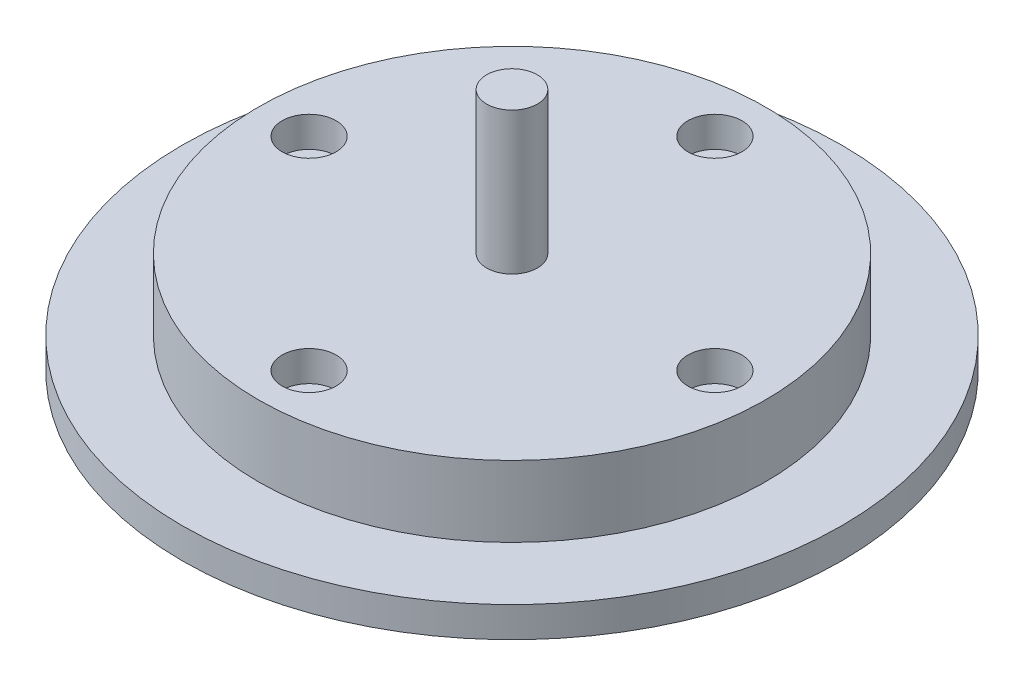
SolidWorks part; units mm, degrees
ref_plane "Front Plane" through (0, 0, 0) normal (0, 0, 1) x (1, 0, 0)
ref_plane "Top Plane" through (0, 0, 0) normal (0, 1, 0) x (1, 0, 0)
ref_plane "Right Plane" through (0, 0, 0) normal (1, 0, 0) x (0, 0, -1)
sketch "Sketch1" plane through (0, 0, 0) normal (0, 1, 0) x (1, 0, 0)
  circle A0 centre (0, 0) radius 25
  circle A1 centre (0, 0) radius 20 construction
  circle A2 centre (0, 20) radius 1.5
  circle A3 centre (20, 0) radius 1.5
  circle A4 centre (0, -20) radius 1.5
  circle A5 centre (-20, 0) radius 1.5
  point P15 (0, 0)
  dimension "D1" = 40
  dimension "D2" = 50
  dimension "D3" = 3
  dimension "D4" = 4
extrude "Boss-Extrude1" add sketch "Sketch1" along normal blind 7
sketch "Sketch2" plane through (0, 7, 0) normal (0, 1, 0) x (1, 0, 0)
  circle A0 centre (0, 20) radius 1.5 construction
  circle A1 centre (0, 20) radius 1.5
  circle A2 centre (-20, 0) radius 1.5 construction
  circle A3 centre (-20, 0) radius 1.5
  circle A4 centre (0, -20) radius 1.5 construction
  circle A5 centre (0, -20) radius 1.5
  circle A6 centre (20, 0) radius 1.5 construction
  circle A7 centre (20, 0) radius 1.5
  circle A8 centre (-20, 0) radius 2.66
  circle A9 centre (0, 20) radius 2.66
  circle A10 centre (20, 0) radius 2.66
  circle A11 centre (0, -20) radius 2.66
  point P22 (0, 0)
  dimension "D1" = 5.32
  dimension "D2" = 4
extrude "Cut-Extrude1" cut sketch "Sketch2" against normal blind 3
sketch "Sketch3" plane through (0, 0, 0) normal (0, 1, 0) x (1, 0, 0)
  circle A0 centre (0, 0) radius 32.5
  circle A1 centre (0, 20) radius 1.5 construction
  circle A2 centre (-20, 0) radius 1.5 construction
  circle A3 centre (0, -20) radius 1.5 construction
  circle A4 centre (20, 0) radius 1.5 construction
  circle A5 centre (0, 20) radius 1.5
  circle A6 centre (-20, 0) radius 1.5
  circle A7 centre (0, -20) radius 1.5
  circle A8 centre (20, 0) radius 1.5
  dimension "D1" = 65
extrude "Boss-Extrude2" add sketch "Sketch3" against normal blind 3
sketch "Sketch4" plane through (0, 7, 0) normal (0, 1, 0) x (1, 0, 0)
  circle A0 centre (0, 0) radius 2.5
  dimension "D1" = 5
extrude "Boss-Extrude3" add sketch "Sketch4" along normal blind 14
